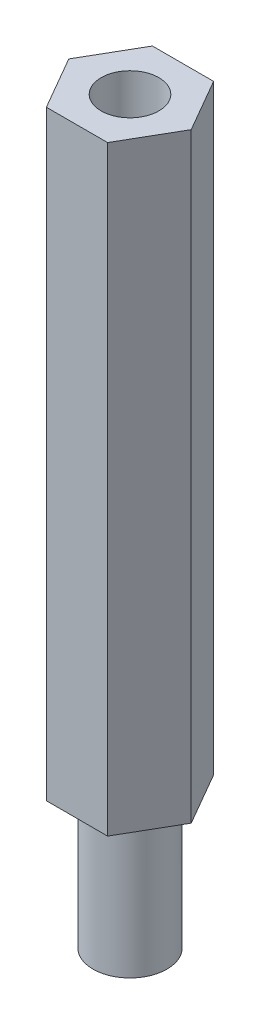
SolidWorks part; units mm, degrees
ref_plane "前视基准面" through (0, 0, 0) normal (0, 0, 1) x (1, 0, 0)
ref_plane "上视基准面" through (0, 0, 0) normal (0, 1, 0) x (1, 0, 0)
ref_plane "右视基准面" through (0, 0, 0) normal (1, 0, 0) x (0, 0, -1)
sketch "草图4" plane through (0, 0, 0) normal (0, 1, 0) x (1, 0, 0)
  line L0 (-12.7945, 0) -> (16.3015, 0) construction
  line L2 (1.325, -2.295) -> (2.65, 0)
  line L3 (2.65, 0) -> (1.325, 2.295)
  line L4 (1.325, 2.295) -> (-1.325, 2.295)
  line L5 (-1.325, 2.295) -> (-2.65, 0)
  line L6 (-2.65, 0) -> (-1.325, -2.295)
  line L7 (-1.325, -2.295) -> (1.325, -2.295)
  circle A0 centre (0, 0) radius 2.295 construction
  dimension "D1" = 5.3
extrude "凸台-拉伸1" add sketch "草图4" along normal blind 26
sketch "草图6" plane through (0, 0, 0) normal (0, -1, 0) x (-1, 0, 0)
  circle A0 centre (0, 0) radius 1.6
  dimension "D1" = 3.2
extrude "凸台-拉伸2" add sketch "草图6" along normal blind 6
cosmetic thread "装饰螺纹线1" parameters "D2"=2.5
sketch "草图7" plane through (0, 26, 0) normal (0, 1, 0) x (1, 0, 0)
  circle A0 centre (0, 0) radius 1.25
  dimension "D1" = 2.5
extrude "切除-拉伸1" cut sketch "草图7" against normal blind 5
cosmetic thread "装饰螺纹线2" parameters "D2"=3
